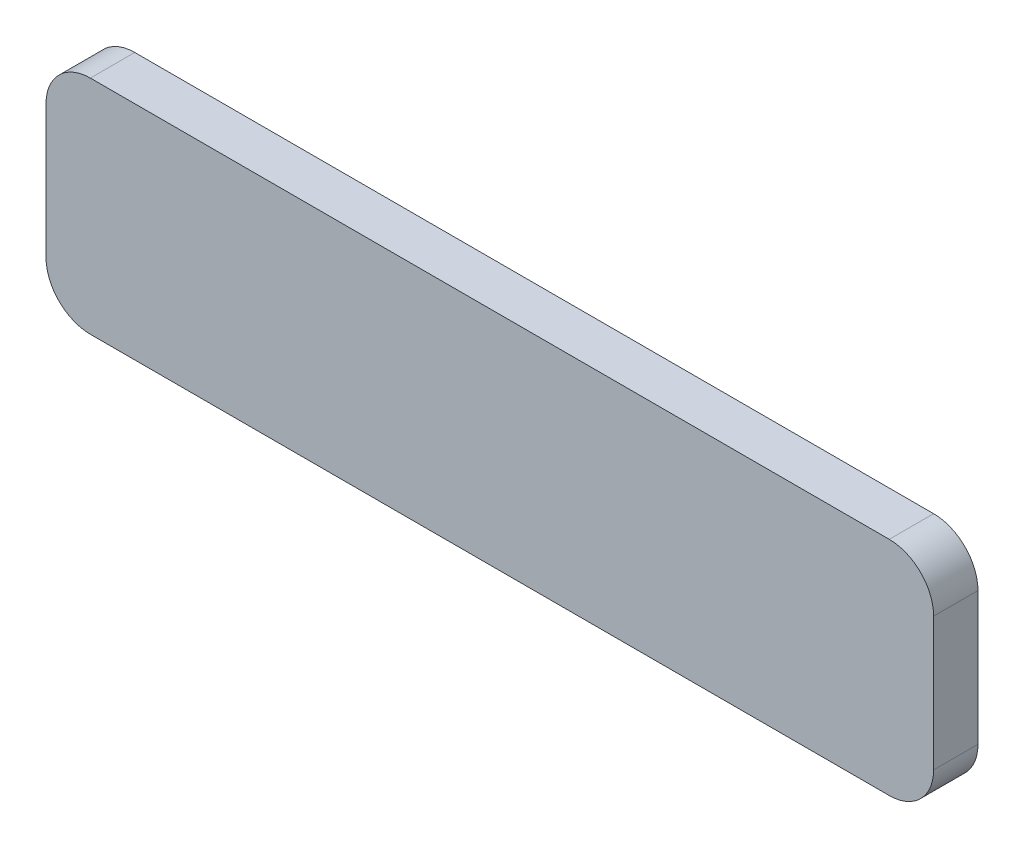
SolidWorks part; units mm, degrees
ref_plane "Front Plane" through (0, 0, 0) normal (0, 0, 1) x (1, 0, 0)
ref_plane "Top Plane" through (0, 0, 0) normal (0, 1, 0) x (1, 0, 0)
ref_plane "Right Plane" through (0, 0, 0) normal (1, 0, 0) x (0, 0, -1)
sketch "Sketch1" plane through (0, 0, 0) normal (0, 0, 1) x (1, 0, 0)
  line L0 (0, 2.5) -> (0, -2.5) construction
  line L1 (-10, 2.5) -> (10, 2.5)
  line L2 (-10, 2.5) -> (-10, -2.5)
  line L3 (-10, -2.5) -> (10, -2.5)
  line L4 (10, 2.5) -> (10, -2.5)
  dimension "D1" = 5
  dimension "D2" = 20
extrude "Boss-Extrude1" add sketch "Sketch1" along normal blind 1
fillet "Fillet1" radius 1 4 edges at (-10, -2.5, 0.5) (10, -2.5, 0.5) (10, 2.5, 0.5) (-10, 2.5, 0.5)
